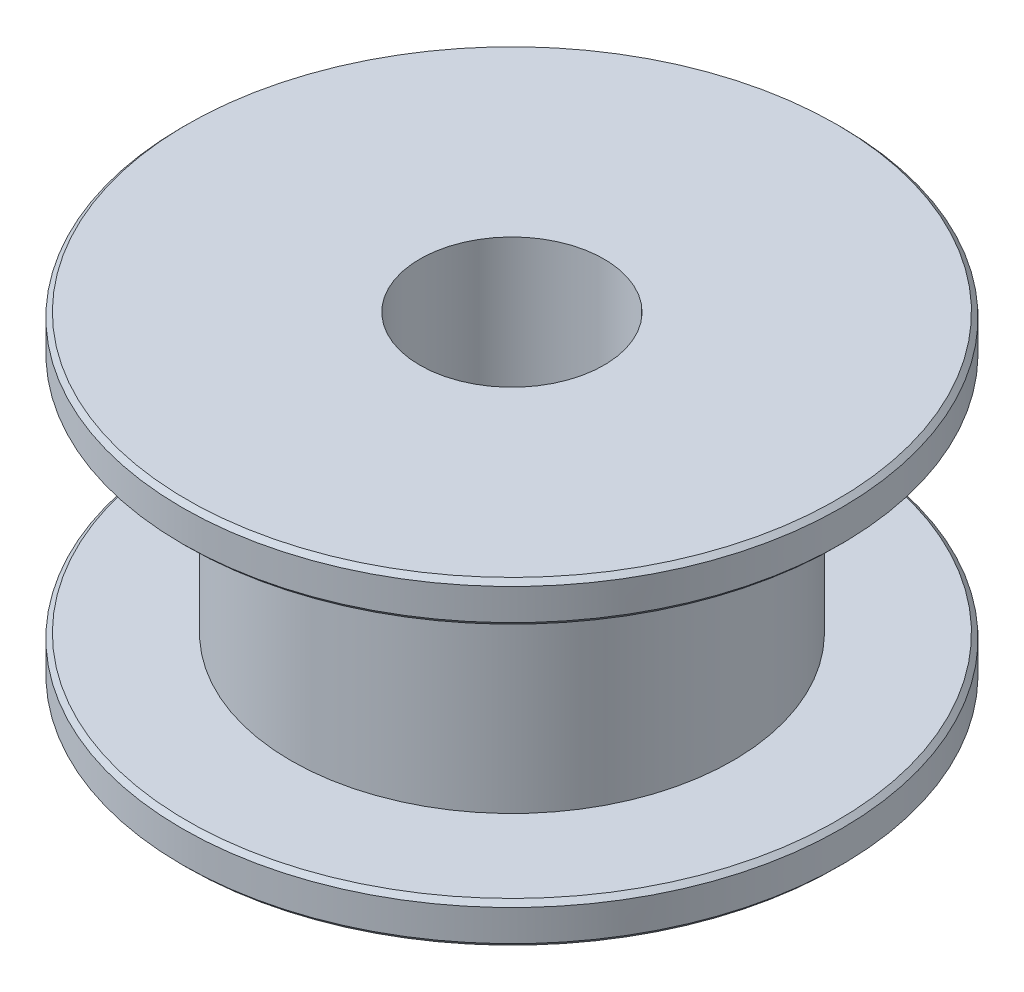
SolidWorks part; units mm, degrees
material "6061 Alloy"
ref_plane "Front Plane" through (0, 0, 0) normal (0, 0, 1) x (1, 0, 0)
ref_plane "Top Plane" through (0, 0, 0) normal (0, 1, 0) x (1, 0, 0)
ref_plane "Right Plane" through (0, 0, 0) normal (1, 0, 0) x (0, 0, -1)
ref_axis "Axis1" through (0, 55, 0) along (0, -1, 0)
sketch "Sketch1" plane through (0, 0, 0) normal (0, 0, 1) x (1, 0, 0)
  line L0 (2.5, 4.325) -> (2.5, -4.325)
  line L1 (2.5, -4.325) -> (8.95, -4.325)
  line L2 (8.95, -4.325) -> (8.95, -3.225)
  line L3 (8.95, -3.225) -> (6, -3.225)
  line L4 (6, -3.225) -> (6, 3.225)
  line L5 (6, 3.225) -> (8.95, 3.225)
  line L6 (8.95, 3.225) -> (8.95, 4.325)
  line L7 (8.95, 4.325) -> (2.5, 4.325)
  line L8 (0, 55) -> (0, -55) construction
  point P2 (2.5, 0)
  point P9 (0, 0)
  dimension "D1" = 8.65
  dimension "D2" = 1.1
  dimension "D3" = 2.5
  dimension "D4" = 6
  dimension "D5" = 8.95
revolve "Revolve1" add sketch "Sketch1" angle 360 about axis through (0, 55, 0) along (0, -1, 0)
chamfer "Chamfer1" distance 0.125 angle 45 4 edges at (0, -4.325, 8.95) (0, -3.225, 8.95) (0, 3.225, 8.95) (0, 4.325, 8.95)
